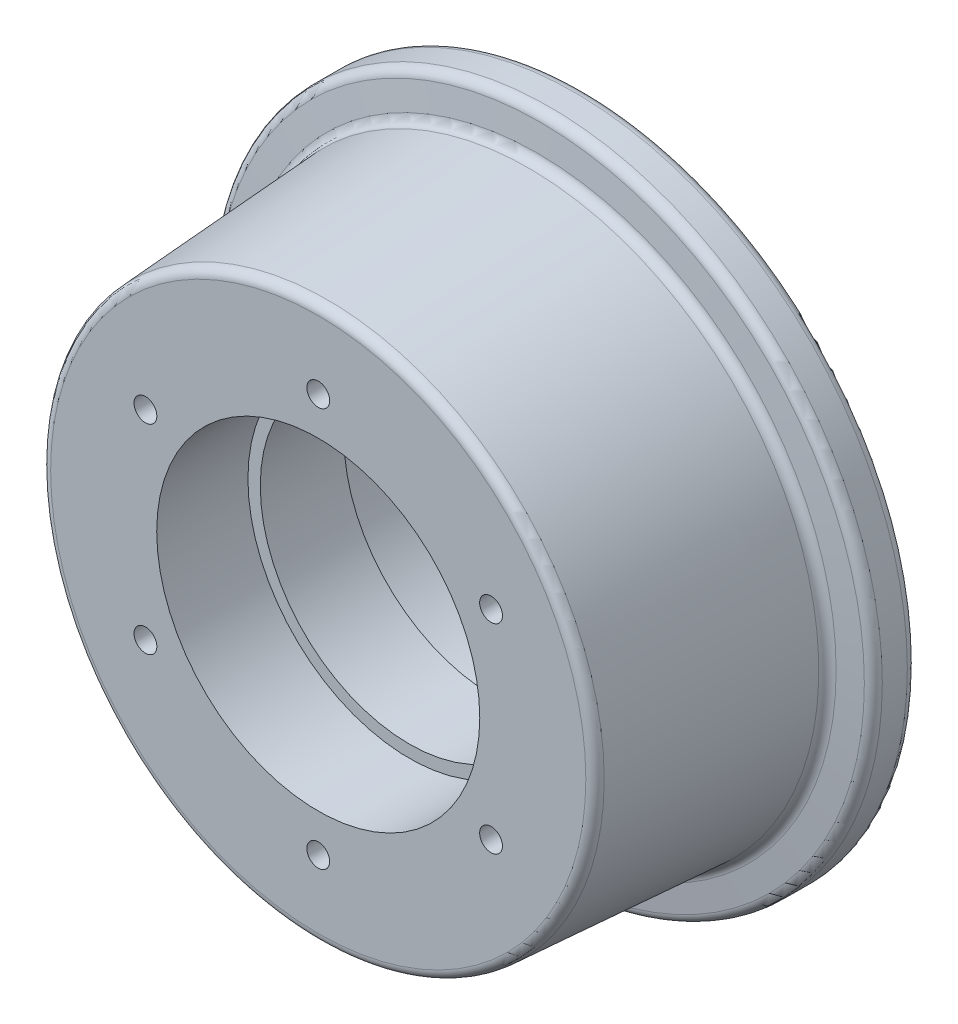
SolidWorks part; units mm, degrees
ref_plane "前视基准面" through (0, 0, 0) normal (0, 0, 1) x (1, 0, 0)
ref_plane "上视基准面" through (0, 0, 0) normal (0, 1, 0) x (1, 0, 0)
ref_plane "右视基准面" through (0, 0, 0) normal (1, 0, 0) x (0, 0, -1)
sketch "草图1" plane through (0, 0, 0) normal (1, 0, 0) x (0, 0, -1)
  line L0 (0, -1000) -> (0, 49000) construction
  line L1 (-1000, 0) -> (49000, 0) construction
  line L2 (-22, 78.5) -> (22, 78.5)
  line L3 (22, 78.5) -> (22, 85)
  line L4 (22, 85) -> (75, 85)
  line L5 (75, 85) -> (75, 140)
  line L6 (-22, 78.5) -> (-22, 85)
  line L7 (-22, 85) -> (-70, 85)
  line L8 (-70, 85) -> (-70, 145.5)
  line L9 (0, 150) -> (0, 0) construction
  line L10 (-70, 145.5) -> (45, 152.8929)
  line L11 (75, 140) -> (70, 140)
  line L12 (70, 140) -> (70, 175)
  line L13 (70, 175) -> (47.3236, 175)
  line L14 (47.3236, 175) -> (45, 152.8929)
  line L15 (47.3236, -825) -> (47.3236, 49175) construction
  dimension "D1" = 44
  dimension "D2" = 78.5
  dimension "D3" = 48
  dimension "D4" = 85
  dimension "D5" = 145.5
  dimension "D6" = 150
  dimension "D7" = 145
  dimension "D8" = 140
  dimension "D9" = 5
  dimension "D10" = 175
  dimension "D11" = 6
  dimension "D12" = 25
revolve "旋转1" add sketch "草图1" angle 360 about L1
fillet "圆角1" radius 5 4 edges at (152.8929, 0, -45) (175, 0, -47.3236) (145.5, 0, 70) (175, 0, -70)
sketch "草图2" plane through (0, 0, -75) normal (0, 0, -1) x (-1, 0, 0)
  line L0 (0, -1000) -> (0, 49000) construction
  circle A0 centre (0, 105) radius 6
  dimension "D1" = 12
  dimension "D2" = 105
extrude "切除-拉伸1" cut sketch "草图2" against normal blind 25
pattern_circular "阵列(圆周)1" count 6 over 360 about axis through (0, 0, 0) along (0, 0, 1) of "切除-拉伸1"
sketch "草图3" plane through (0, 0, 70) normal (0, 0, 1) x (1, 0, 0)
  line L0 (0, -1000) -> (0, 49000) construction
  circle A0 centre (0, 105) radius 6
  dimension "D2" = 12
  dimension "D1" = 105
extrude "切除-拉伸2" cut sketch "草图3" against normal blind 25
pattern_circular "阵列(圆周)2" count 6 over 360 about axis through (0, 0, 0) along (0, 0, 1) of "切除-拉伸2"
